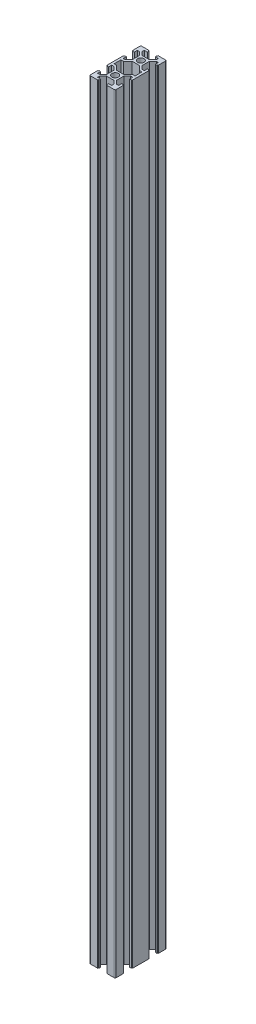
SolidWorks part; units mm, degrees
ref_plane "Front Plane" through (0, 0, 0) normal (0, 0, 1) x (1, 0, 0)
ref_plane "Top Plane" through (0, 0, 0) normal (0, 1, 0) x (1, 0, 0)
ref_plane "Right Plane" through (0, 0, 0) normal (1, 0, 0) x (0, 0, -1)
sketch "Sketch1" plane through (0, 0, 0) normal (0, 1, 0) x (1, 0, 0)
  line L0 (30, 20) -> (10, 20) construction
  line L1 (23.9, 20) -> (23.9, 17.1607)
  line L2 (30, 10.75) -> (30, 16.4)
  line L3 (30, 29.25) -> (30, 23.6)
  line L4 (16.1, 20) -> (16.1, 17.1607)
  line L5 (20, 30) -> (20, -10) construction
  line L6 (20, 20) -> (30, 30) construction
  line L7 (28.2, 25.5) -> (28.2, 23.1)
  line L8 (17.1607, 16.1) -> (13.7607, 12.7)
  line L9 (17.1607, 23.9) -> (22.8393, 23.9)
  line L10 (23.9, 22.8393) -> (23.9, 20)
  line L11 (17.1607, 16.1) -> (22.8393, 16.1)
  line L12 (16.1, 23.9) -> (23.9, 16.1) construction
  line L13 (23.9, 23.9) -> (16.1, 16.1) construction
  line L14 (25.5, 30) -> (23.6, 30)
  line L15 (14.5, 26.5607) -> (17.1607, 23.9)
  line L16 (23.1, 28.2) -> (25.5, 28.2)
  line L17 (29.5, 23.1) -> (28.2, 23.1)
  line L18 (14.5, 28.2) -> (14.5, 26.5607)
  line L19 (29.25, 30) -> (25.5, 30)
  line L20 (25.5, 28.2) -> (25.5, 26.5607)
  line L21 (28.2, 25.5) -> (26.5607, 25.5)
  line L22 (23.1, 29.5) -> (23.1, 28.2)
  line L23 (16.9, 28.2) -> (14.5, 28.2)
  line L24 (22.8393, 16.1) -> (26.2393, 12.7)
  line L25 (25.5, 26.5607) -> (22.8393, 23.9)
  line L26 (26.5607, 25.5) -> (23.9, 22.8393)
  line L27 (16.9, 29.5) -> (16.9, 28.2)
  line L28 (29.5, 23.1) -> (29.5, 23.6)
  line L29 (30, 23.6) -> (29.5, 23.6)
  line L30 (23.6, 30) -> (23.6, 29.5)
  line L31 (23.1, 29.5) -> (23.6, 29.5)
  line L32 (16.9, 29.5) -> (16.4, 29.5)
  line L33 (16.4, 30) -> (16.4, 29.5)
  line L34 (14.5, 30) -> (16.4, 30)
  line L35 (10.75, 30) -> (14.5, 30)
  line L36 (10, 29.25) -> (10, 23.6)
  line L37 (10, 23.6) -> (10.5, 23.6)
  line L38 (10.5, 23.1) -> (10.5, 23.6)
  line L39 (10.5, 23.1) -> (11.8, 23.1)
  line L40 (11.8, 25.5) -> (11.8, 23.1)
  line L41 (11.8, 25.5) -> (13.4393, 25.5)
  line L42 (13.4393, 25.5) -> (16.1, 22.8393)
  line L43 (16.1, 22.8393) -> (16.1, 20)
  line L44 (30, 16.4) -> (29.5, 16.4)
  line L45 (29.5, 16.9) -> (29.5, 16.4)
  line L46 (29.5, 16.9) -> (28.2, 16.9)
  line L47 (28.2, 14.5) -> (28.2, 16.9)
  line L48 (28.2, 14.5) -> (26.5607, 14.5)
  line L49 (26.5607, 14.5) -> (23.9, 17.1607)
  line L50 (28.2, 12.7) -> (28.2, 7.3)
  line L51 (28.2, 12.7) -> (26.2393, 12.7)
  line L52 (30, 10.75) -> (30, 9.25)
  line L53 (13.4393, 14.5) -> (16.1, 17.1607)
  line L54 (11.8, 12.7) -> (13.7607, 12.7)
  line L55 (11.8, 12.7) -> (11.8, 7.3)
  line L56 (11.8, 14.5) -> (13.4393, 14.5)
  line L57 (11.8, 14.5) -> (11.8, 16.9)
  line L58 (10.5, 16.9) -> (11.8, 16.9)
  line L59 (10.5, 16.9) -> (10.5, 16.4)
  line L60 (10, 16.4) -> (10.5, 16.4)
  line L61 (10, 10.75) -> (10, 16.4)
  line L62 (10, 10.75) -> (10, 9.25)
  line L63 (30, 10) -> (10, 10) construction
  line L64 (23.9, -3.9) -> (16.1, 3.9) construction
  line L65 (16.1, -3.9) -> (23.9, 3.9) construction
  line L66 (20, 0) -> (30, -10) construction
  line L67 (30, 0) -> (10, 0) construction
  line L68 (10, 9.25) -> (10, 3.6)
  line L69 (10, 3.6) -> (10.5, 3.6)
  line L70 (10.5, 3.1) -> (10.5, 3.6)
  line L71 (10.5, 3.1) -> (11.8, 3.1)
  line L72 (11.8, 5.5) -> (11.8, 3.1)
  line L73 (11.8, 5.5) -> (13.4393, 5.5)
  line L74 (11.8, 7.3) -> (13.7607, 7.3)
  line L75 (13.4393, 5.5) -> (16.1, 2.8393)
  line L76 (28.2, 7.3) -> (26.2393, 7.3)
  line L77 (26.5607, 5.5) -> (23.9, 2.8393)
  line L78 (28.2, 5.5) -> (26.5607, 5.5)
  line L79 (28.2, 5.5) -> (28.2, 3.1)
  line L80 (29.5, 3.1) -> (28.2, 3.1)
  line L81 (29.5, 3.1) -> (29.5, 3.6)
  line L82 (30, 3.6) -> (29.5, 3.6)
  line L83 (16.1, -2.8393) -> (16.1, 0)
  line L84 (13.4393, -5.5) -> (16.1, -2.8393)
  line L85 (11.8, -5.5) -> (13.4393, -5.5)
  line L86 (11.8, -5.5) -> (11.8, -3.1)
  line L87 (10.5, -3.1) -> (11.8, -3.1)
  line L88 (10.5, -3.1) -> (10.5, -3.6)
  line L89 (10, -3.6) -> (10.5, -3.6)
  line L90 (10, -9.25) -> (10, -3.6)
  line L91 (10.75, -10) -> (14.5, -10)
  line L92 (14.5, -10) -> (16.4, -10)
  line L93 (16.4, -10) -> (16.4, -9.5)
  line L94 (16.9, -9.5) -> (16.4, -9.5)
  line L95 (23.1, -9.5) -> (23.6, -9.5)
  line L96 (23.6, -10) -> (23.6, -9.5)
  line L97 (30, -3.6) -> (29.5, -3.6)
  line L98 (29.5, -3.1) -> (29.5, -3.6)
  line L99 (16.9, -9.5) -> (16.9, -8.2)
  line L100 (26.5607, -5.5) -> (23.9, -2.8393)
  line L101 (25.5, -6.5607) -> (22.8393, -3.9)
  line L102 (22.8393, 3.9) -> (26.2393, 7.3)
  line L103 (16.9, -8.2) -> (14.5, -8.2)
  line L104 (23.1, -9.5) -> (23.1, -8.2)
  line L105 (28.2, -5.5) -> (26.5607, -5.5)
  line L106 (25.5, -8.2) -> (25.5, -6.5607)
  line L107 (29.25, -10) -> (25.5, -10)
  line L108 (14.5, -8.2) -> (14.5, -6.5607)
  line L109 (29.5, -3.1) -> (28.2, -3.1)
  line L110 (23.1, -8.2) -> (25.5, -8.2)
  line L111 (14.5, -6.5607) -> (17.1607, -3.9)
  line L112 (25.5, -10) -> (23.6, -10)
  line L113 (17.1607, 3.9) -> (22.8393, 3.9)
  line L114 (23.9, -2.8393) -> (23.9, 0)
  line L115 (17.1607, -3.9) -> (22.8393, -3.9)
  line L116 (17.1607, 3.9) -> (13.7607, 7.3)
  line L117 (28.2, -5.5) -> (28.2, -3.1)
  line L118 (16.1, 0) -> (16.1, 2.8393)
  line L119 (30, -9.25) -> (30, -3.6)
  line L120 (30, 9.25) -> (30, 3.6)
  line L121 (23.9, 0) -> (23.9, 2.8393)
  arc A0 (22.5, 20) -> (17.5, 20) centre (20, 20) cw
  arc A1 (29.25, 30) -> (30, 29.25) centre (29.25, 29.25) cw
  arc A2 (22.5, 20) -> (17.5, 20) centre (20, 20) ccw
  arc A3 (10.75, 30) -> (10, 29.25) centre (10.75, 29.25) ccw
  arc A4 (10.75, -10) -> (10, -9.25) centre (10.75, -9.25) cw
  arc A5 (22.5, 0) -> (17.5, 0) centre (20, 0) cw
  arc A6 (29.25, -10) -> (30, -9.25) centre (29.25, -9.25) ccw
  arc A7 (22.5, 0) -> (17.5, 0) centre (20, 0) ccw
  point P39 (20, 23.9)
  point P65 (20, 16.1)
  point P85 (20, 10)
  point P103 (11.8, 10)
  point P108 (28.2, 10)
  point P149 (20, 3.9)
  point P150 (20, -3.9)
  dimension "D3" = 7.8
  dimension "D14" = 0.75
  dimension "D2" = 20
  dimension "D4" = 7.8
  dimension "D5" = 0.5
  dimension "D6" = 1.5
  dimension "D7" = 0.5
  dimension "D8" = 5.5
  dimension "D9" = 5.5
  dimension "D10" = 3.1
  dimension "D11" = 3.1
  dimension "D12" = 0.5
  dimension "D13" = 0.5
extrude "Boss-Extrude2" add sketch "Sketch1" along normal blind 600
